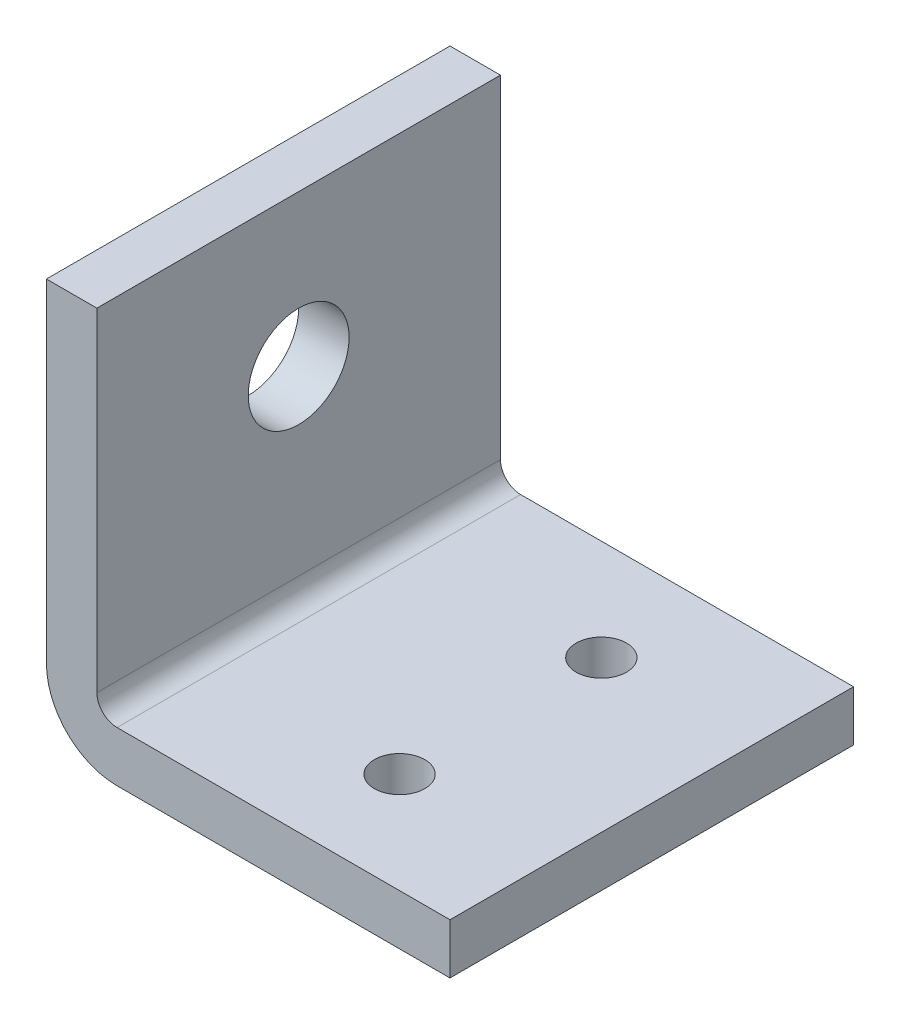
SolidWorks part; units mm, degrees
ref_plane "Front Plane" through (0, 0, 0) normal (0, 0, 1) x (1, 0, 0)
ref_plane "Top Plane" through (0, 0, 0) normal (0, 1, 0) x (1, 0, 0)
ref_plane "Right Plane" through (0, 0, 0) normal (1, 0, 0) x (0, 0, -1)
sketch "Sketch1" plane through (0, 0, 0) normal (0, 0, 1) x (1, 0, 0)
  line L1 (0, 0) -> (40, 0)
  line L2 (0, 0) -> (0, 40)
  line L3 (0, 40) -> (40, 40)
  line L4 (40, 0) -> (40, 40)
  dimension "D1" = 40
  dimension "D2" = 40
extrude "Boss-Extrude1" add sketch "Sketch1" along normal mid plane 40
sketch "Sketch2" plane through (0, 0, 20) normal (0, 0, 1) x (1, 0, 0)
  line L0 (0, 0) -> (40, 0) construction
  line L1 (40, 40) -> (5, 40)
  line L2 (40, 40) -> (40, 5)
  line L3 (40, 5) -> (5, 5)
  line L4 (5, 40) -> (5, 5)
  line L5 (0, 40) -> (0, 0) construction
  dimension "D1" = 5
  dimension "D2" = 5
extrude "Cut-Extrude1" cut sketch "Sketch2" against normal blind 40
fillet "Fillet1" radius 2 1 edges at (5, 5, 0)
fillet "Fillet2" radius 7 1 edges at (0, 0, 0)
hole_wizard "Hole1" positions "Sketch3" profile "Sketch4" legacy end condition through all
sketch "Sketch3" plane through (5, 0, 0) normal (1, 0, 0) x (0, 0, -1)
  line L0 (-20, 0) -> (20, 0) construction
  point P0 (0, 25)
  dimension "D1" = 25
sketch "Sketch4" plane through (5, 25, 0) normal (0, 1, 0) x (0, 0, -1)
  line L0 (0, 0) -> (0, 5)
  line L1 (0, 5) -> (5, 5)
  line L2 (5, 5) -> (5, 0)
  line L3 (5, 0) -> (0, 0)
  line L4 (0, 110) -> (0, -10) construction
  dimension "Diameter" = 10
  dimension "Depth" = 5
hole_wizard "Hole2" positions "Sketch5" profile "Sketch6" legacy end condition through all
sketch "Sketch5" plane through (0, 5, 0) normal (0, 1, 0) x (1, 0, 0)
  line L0 (40, 20) -> (40, -20) construction
  point P0 (25, -10)
  dimension "D1" = 15
  dimension "D2" = 10
sketch "Sketch6" plane through (25, 5, 10) normal (1, 0, 0) x (0, 0, 1)
  line L0 (0, 0) -> (0, 5)
  line L1 (0, 5) -> (2.5, 5)
  line L2 (2.5, 5) -> (2.5, 0)
  line L3 (2.5, 0) -> (0, 0)
  line L4 (0, 110) -> (0, -10) construction
  dimension "Diameter" = 5
  dimension "Depth" = 5
mirror "Mirror1" about plane through (0, 0, 0) normal (0, 0, 1) of "Hole2"
